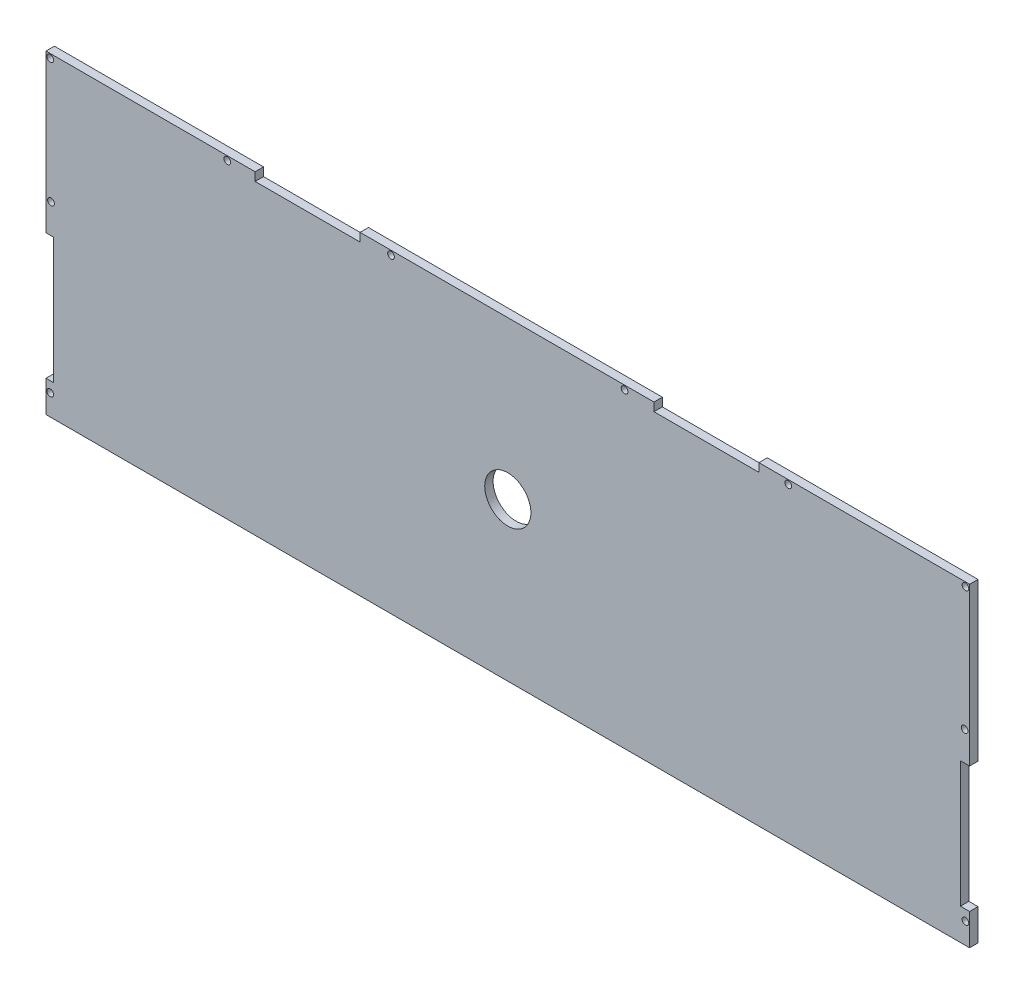
SolidWorks part; units mm, degrees
ref_plane "Plan de face" through (0, 0, 0) normal (0, 0, 1) x (1, 0, 0)
ref_plane "Plan de dessus" through (0, 0, 0) normal (0, 1, 0) x (1, 0, 0)
ref_plane "Plan de droite" through (0, 0, 0) normal (1, 0, 0) x (0, 0, -1)
sketch "Esquisse1" plane through (0, 0, 0) normal (0, 0, 1) x (1, 0, 0)
  line L1 (220, -75) -> (-220, -75)
  line L2 (220, -75) -> (220, 75)
  line L3 (220, 75) -> (-220, 75)
  line L4 (-220, -75) -> (-220, 75)
  line L5 (220, -75) -> (-220, 75) construction
  line L6 (220, 75) -> (-220, -75) construction
  point P0 (0, 0)
  dimension "D1" = 440
  dimension "D2" = 150
extrude "Boss.-Extru.1" add sketch "Esquisse1" along normal blind 4
sketch "Esquisse2" plane through (0, 0, 0) normal (0, 0, -1) x (-1, 0, 0)
  line L0 (0, 75) -> (0, -75) construction
  line L1 (-220, 75) -> (220, 75) construction
  line L2 (220, -75) -> (-220, -75) construction
  line L3 (220, 0) -> (-220, 0) construction
  line L4 (220, 75) -> (220, -75) construction
  line L5 (-220, -75) -> (-220, 75) construction
  circle A1 centre (0, 0) radius 11
  dimension "D2" = 22
extrude "Enlèv. mat.-Extru.1" cut sketch "Esquisse2" against normal blind 10
sketch "Esquisse3" plane through (0, 0, 0) normal (0, 0, -1) x (-1, 0, 0)
  line L0 (220, 75) -> (220, -75) construction
  line L1 (216.3751, -60) -> (220, -60)
  line L2 (216.3751, -60) -> (216.3751, 0)
  line L3 (216.3751, 0) -> (220, 0)
  line L4 (220, -60) -> (220, 0)
  line L5 (-220, -75) -> (-220, 75) construction
  line L6 (-215.6249, -60) -> (-220, -60)
  line L7 (-215.6249, -60) -> (-215.6249, 0)
  line L8 (-215.6249, 0) -> (-220, 0)
  line L9 (-220, -60) -> (-220, 0)
  line L10 (-220, 75) -> (220, 75) construction
  line L11 (70.3751, 71) -> (120.3751, 71)
  line L12 (70.3751, 71) -> (70.3751, 75)
  line L13 (70.3751, 75) -> (120.3751, 75)
  line L14 (120.3751, 71) -> (120.3751, 75)
  line L15 (120.3751, 71) -> (120.3751, 75) construction
  line L16 (-69.6249, 71) -> (-69.6249, 75) construction
  line L17 (-119.6249, 71) -> (-69.6249, 71)
  line L18 (-119.6249, 71) -> (-119.6249, 75)
  line L19 (-119.6249, 75) -> (-69.6249, 75)
  line L20 (-69.6249, 71) -> (-69.6249, 75)
  point P30 (0, 0)
extrude "Enlèv. mat.-Extru.2" cut sketch "Esquisse3" against normal blind 4
sketch "Esquisse4" plane through (0, 0, 0) normal (0, 0, -1) x (-1, 0, 0)
  line L0 (-219.6249, 0) -> (-219.6249, -60) construction
  line L1 (-220, 75) -> (-119.6249, 75) construction
  line L2 (-69.6249, 75) -> (70.3751, 75) construction
  line L3 (-69.6249, 71) -> (-69.6249, 75) construction
  line L4 (-119.6249, 75) -> (-119.6249, 71) construction
  line L5 (-220, 0) -> (-220, 75) construction
  line L10 (-215.6249, 0) -> (-220, 0) construction
  line L11 (-220, -60) -> (-215.6249, -60) construction
  line L12 (-220, -75) -> (-220, -60) construction
  line L13 (0, -36.0382) -> (0, 131.4068) construction
  circle A0 centre (-217.6249, 14) radius 1.6
  circle A1 centre (-218, 73) radius 1.6
  circle A2 centre (-218, -65) radius 1.6
  circle A3 centre (-133.6249, 73) radius 1.6
  circle A4 centre (-55.6249, 73) radius 1.6
  circle A8 centre (55.6249, 73) radius 1.6
  circle A9 centre (133.6249, 73) radius 1.6
  circle A10 centre (218, -65) radius 1.6
  circle A11 centre (218, 73) radius 1.6
  circle A12 centre (217.6249, 14) radius 1.6
  dimension "D1" = 3.2
  dimension "D3" = 3.2
  dimension "D4" = 2
  dimension "D5" = 3.2
  dimension "D6" = 2
  dimension "D7" = 3.2
  dimension "D8" = 2
  dimension "D11" = 14
  dimension "D12" = 14
  dimension "D13" = 2
  dimension "D22" = 3.2
  dimension "D23" = 5
  dimension "D24" = 2
  dimension "D2" = 2
  dimension "D21" = 14
extrude "Enlèv. mat.-Extru.3" cut sketch "Esquisse4" against normal blind 4
